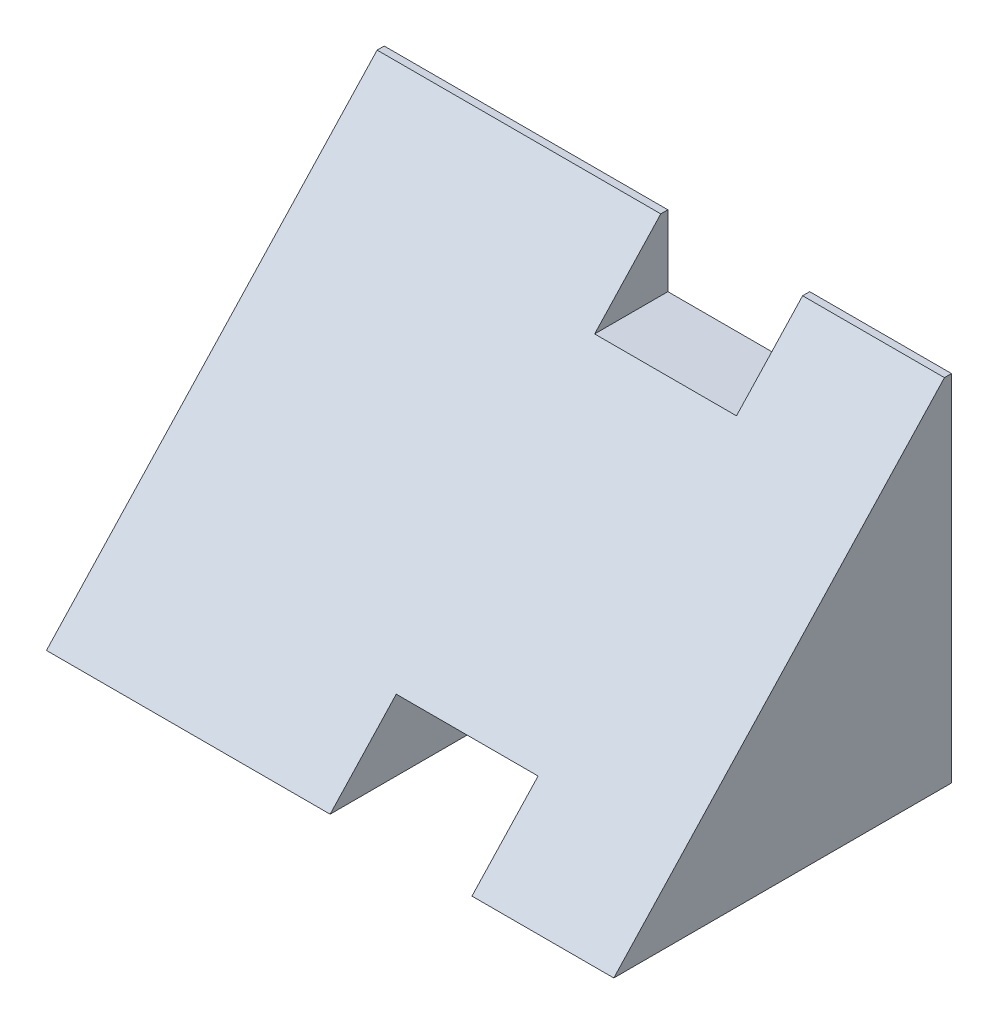
SolidWorks part; units mm, degrees
ref_plane "前视基准面" through (0, 0, 0) normal (0, 0, 1) x (1, 0, 0)
ref_plane "上视基准面" through (0, 0, 0) normal (0, 1, 0) x (1, 0, 0)
ref_plane "右视基准面" through (0, 0, 0) normal (1, 0, 0) x (0, 0, -1)
sketch "草图1" plane through (0, 0, 0) normal (0, 0, 1) x (1, 0, 0)
  line L0 (-9.6443, 0) -> (30.3557, 0)
  line L1 (30.3557, -10) -> (50.3557, -10)
  line L2 (50.3557, -10) -> (50.3557, 0)
  line L3 (50.3557, 0) -> (70.3557, 0)
  line L4 (70.3557, 0) -> (70.3557, -50)
  line L5 (70.3557, -50) -> (50.3557, -50)
  line L6 (50.3557, -50) -> (50.3557, -40)
  line L7 (50.3557, -40) -> (30.3557, -40)
  line L8 (30.3557, -40) -> (30.3557, -50)
  line L9 (30.3557, -50) -> (-9.6443, -50)
  line L10 (-9.6443, -50) -> (-9.6443, 0)
  line L11 (30.3557, 0) -> (30.3557, -10)
  dimension "D1" = 50
  dimension "D2" = 50
  dimension "D3" = 10
  dimension "D4" = 10
  dimension "D5" = 20
  dimension "D6" = 20
  dimension "D7" = 20
  dimension "D8" = 20
  dimension "D9" = 40
extrude "凸台-拉伸1" add sketch "草图1" along normal blind 1
draft "拔模5" type of draft neutral plane draft angle 43 faces to draft 1 face at (37.0224, -25, 1) neutral plane through (-9.6443, 0, 1) neutral plane normal (0, 1, 0) parameters "D1"=43
